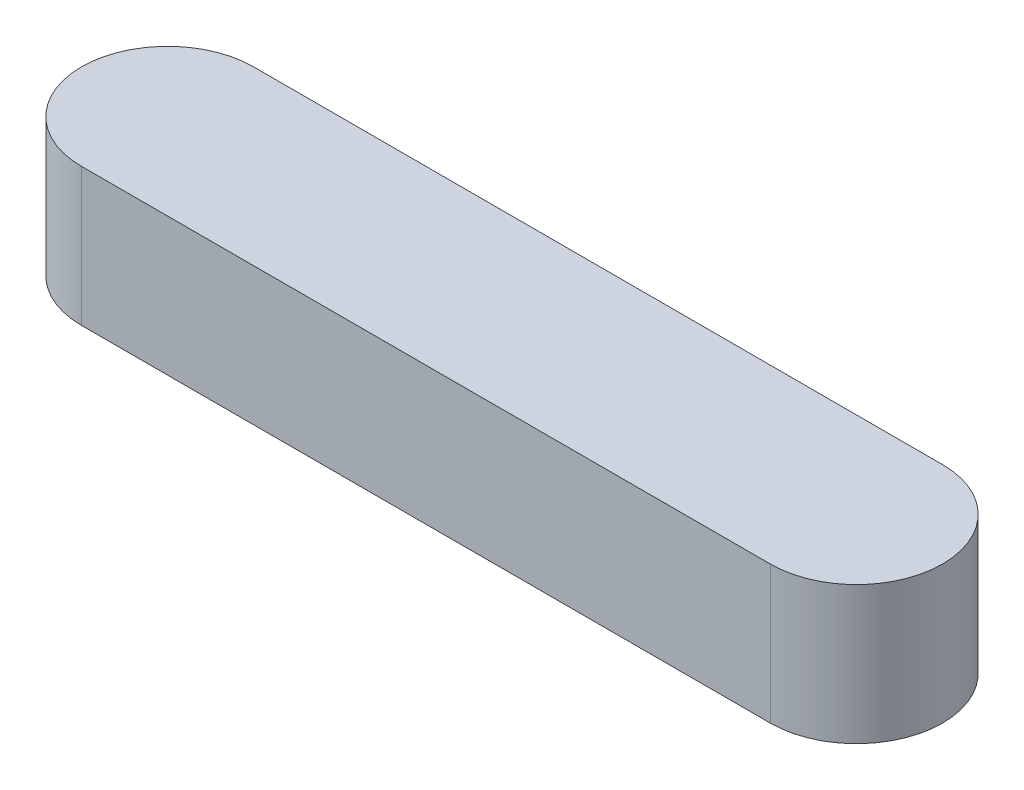
SolidWorks part; units mm, degrees
ref_plane "Front Plane" through (0, 0, 0) normal (0, 0, 1) x (1, 0, 0)
ref_plane "Top Plane" through (0, 0, 0) normal (0, 1, 0) x (1, 0, 0)
ref_plane "Right Plane" through (0, 0, 0) normal (1, 0, 0) x (0, 0, -1)
sketch "Sketch1" plane through (0, 0, 0) normal (0, 1, 0) x (1, 0, 0)
  line L0 (-20, 0) -> (20, 0) construction
  line L1 (-20, 5) -> (20, 5)
  line L2 (-20, -5) -> (20, -5)
  arc A0 (-20, 5) -> (-20, -5) centre (-20, 0) ccw
  arc A1 (20, -5) -> (20, 5) centre (20, 0) ccw
  point P2 (0, 0)
  point P8 (-25, 0)
  point P9 (25, 0)
  dimension "D2" = 5
  dimension "D1" = 50
extrude "Boss-Extrude1" add sketch "Sketch1" along normal blind 8
